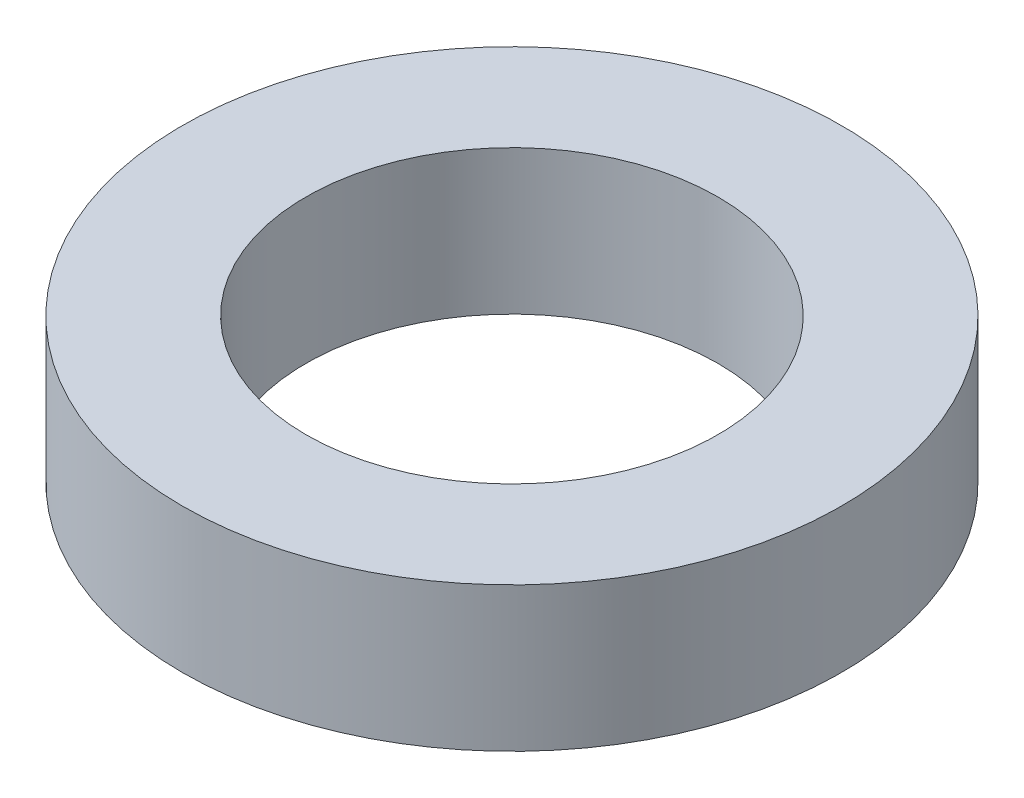
SolidWorks part; units mm, degrees
ref_plane "Front Plane" through (0, 0, 0) normal (0, 0, 1) x (1, 0, 0)
ref_plane "Top Plane" through (0, 0, 0) normal (0, 1, 0) x (1, 0, 0)
ref_plane "Right Plane" through (0, 0, 0) normal (1, 0, 0) x (0, 0, -1)
sketch "Sketch1" plane through (0, 0, 0) normal (0, 1, 0) x (1, 0, 0)
  circle A0 centre (0, 0) radius 16
  circle A1 centre (0, 0) radius 10
  dimension "D1" = 20
  dimension "D2" = 32
extrude "Boss-Extrude1" add sketch "Sketch1" along normal mid plane 7
equation "\"Ns\"= 20"
equation "\"Np_b\"= 26"
equation "\"Np_s\"= 22"
equation "\"Nr_b\"= \"Ns\" + \"Np_b\" * 2"
equation "\"num_planet\"= 4"
equation "\"module\"= 1"
equation "\"fw_p_b\"= 8"
equation "\"fw_r_b\"= \"fw_p_b\"'face width"
equation "\"fw_s_calc\"= 10mm'face width"
equation "\"fw_r_s\"= 8mm'face width"
equation "\"fw_p_s\"= \"fw_r_s\" + \"clearance_planet\""
equation "\"fw_s_used\"= \"fw_p_s\" + \"fw_p_b\" + \"clearance_planet\" + \"sec_carrier_thickness\" + \"standard_clearance_1_5mm\" - \"carrier_small_ring_inner_bearing_flap\" +  \"standard_clearance_1_5mm\" "
equation "\"pressure_angle\"= 20deg"
equation "\"motor_OD\"= 72"
equation "\"motor_height\"= 27"
equation "\"motor_mount_hole_PCD\"= 32"
equation "\"motor_mount_hole_dia\"= 4"
equation "\"motor_mount_hole_num\"= 4"
equation "\"wire_slot_dist_from_center\"= 33"
equation "\"wire_slot_length\"= 10"
equation "\"wire_slot_radius\"= 4"
equation "\"motor_output_hole_PCD\"= 22"
equation "\"motor_output_hole_dia\"= 3"
equation "\"motor_output_hole_num\"= 4"
equation "\"h_a\"= 1 * \"module\"'addendum"
equation "\"h_f\"= 1.25 * \"module\"'dedendum"
equation "\"clr_tip_root\"= \"h_f\" - \"h_a\"'clearance of gear tooth tip and root"
equation "\"dp_r_b\"= \"module\" * \"Nr_b\"'PCD"
equation "\"db_r_b\"= \"dp_r_b\" * cos ( \"pressure_angle\" )'base CD"
equation "\"alpha_r_b\"= sqr ( \"dp_r_b\" ^ 2 - \"db_r_b\" ^ 2 ) / \"db_r_b\" * 180 / pi - \"pressure_angle\""
equation "\"beta_r_b\"= ( 360 / ( 4 * \"Nr_b\" ) + \"alpha_r_b\" ) * 2"
equation "\"bearing_ID\"= \"module\" * ( \"Ns\" + \"Np_b\") + 6"
equation "\"bearing_OD\"= 1.18 * \"bearing_ID\" + 8.57"
equation "\"bearing_height\"= 0.09 * \"bearing_ID\" + 4.62"
equation "\"clearance_planet\"=1.5"
equation "\"case_dist\"= \"sec_carrier_thickness\" + \"clearance_planet\" + \"sun_coupler_hub_thickness\" - \"case_mounting_surface_height\""
equation "\"Motor_case_OD_max\"= \"case_mounting_PCD\" + \"case_mounting_hole_allen_socket_dia\" + \"clearance_case_mount_holes_shell_thickness\" * 2"
equation "\"case_mounting_PCD\"= \"motor_case_OD_base\" + \"case_mounting_hole_shift\" * 2"
equation "\"bearing mount thickness\"= IIF((\"bearing_OD\" + \"output_mounting_hole_dia\" * 4) > (\"Nr_s\" * \"module\" + 2 * \"h_b\"), \"output_mounting_hole_dia\" * 2, ((\"Nr_s\" * \"module\" + 2 * \"h_b\" - (\"bearing_OD\" + \"output_mounting_hole_dia\" * 4)) / 2) + \"output_mounting_hole_dia\" * 2 + \"standard_clearance_1_5mm\")"
equation "\"case_mounting_hole_dia\"=3"
equation "\"output_mounting_PCD\"= \"bearing_OD\" + \"bearing mount thickness\""
equation "\"output_mounting_hole_dia\"= 4"
equation "\"clearance_case_mount_holes_shell_thickness\"= 1"
equation "\"motor_case_OD_base\"= \"motor_OD\" + \"clearance_motor_and_case\" * 2 + \"Motor_case_thickness\" * 2"
equation "\"sec_carrier_thickness\"= 5"
equation "\"sun_coupler_hub_thickness\"= 4"
equation "\"clearance_sun_coupler_sec_carrier\"= 1.5"
equation "\"clearance_motor_and_case\"= IIF( ((\"Ns\" + \"Np_b\" * 2) * \"module\") < \"motor_OD\", 5, (((\"Ns\" + \"Np_b\" * 2) * \"module\" - \"motor_OD\") * 0.5 + 5) )"
equation "\"Motor_case_thickness\"= 2.5"
equation "\"Motor_case_ID\"= \"motor_OD\" + \"clearance_motor_and_case\" * 2"
equation "\"case_mounting_hole_shift\"= \"case_mounting_hole_dia\" / 2 - 0.5"
equation "\"output_mounting_nut_wrench_size\"= 7"
equation "\"output_mounting_nut_thickness\"= 3.2"
equation "\"case_mounting_hole_allen_socket_dia\"= 5.5"
equation "\"output_mounting_nut_depth\"= 3"
equation "\"case_mounting_bolt_depth\"= 4.5"
equation "\"ring_radial_thickness\"= 5"
equation "\"ring_OD_b\"= \"Nr_b\" * \"module\" + \"ring_radial_thickness\" * 2"
equation "\"ring_to_chamfer_clearance\"= \"clearance_planet\""
equation "\"Motor_case_OD_base_to_chamfer\"=5"
equation "\"pattern_offset_from_motor_case_OD_base\"= 3"
equation "\"pattern_bulge_dia\"= 3"
equation "\"pattern_num_bulge\"= 18"
equation "\"pattern_depth\"= 2"
equation "\"case_mounting_wrench_size\"= 5.5"
equation "\"case_mounting_nut_clearance\"= 2"
equation "\"base_plate_thickness\"= 4"
equation "\"case_mounting_nut_thickness\"= 2.4"
equation "\"case_mounting_surface_height\"= 4"
equation "\"central_hole_offset_from_motor_mount_PCD\"= 5"
equation "\"driver_upper_holes_dist_from_center\"= 23"
equation "\"driver_lower_holes_dist_from_center\"= 15"
equation "\"driver_side_holes_dist_from_center\"= 20"
equation "\"driver_mount_holes_dia\"= 2.5"
equation "\"driver_mount_inserts_OD\"= 3.5"
equation "\"driver_mount_thickness\"= 1.5"
equation "\"driver_mount_height\"= 4"
equation "\"air_flow_hole_offset\"= 3"
equation "\"pressure angle\"= 20deg"
equation "\"h_b\"= 1.25 * \"module\"'dedendum"
equation "\"planet_pin_bolt_dia\"= 5"
equation "\"planet_pin_socket_head_dia\"= 8.5"
equation "\"carrier_PCD\"= ( \"Np_b\" + \"Ns\" ) * \"module\""
equation "\"planet_shaft_dia\"= 8"
equation "\"planet_shaft_step_offset\"= 1"
equation "\"carrier_trapezoidal_support_sun_offset\"= 5"
equation "\"carrier_trapezoidal_support_hole_PCD_offset_bearing_ID\"= 4"
equation "\"carrier_trapezoidal_support_hole_dia\"= 3"
equation "\"carrier_trapezoidal_support_hole_socket_head_dia\"= 5.5"
equation "\"carrier_bearing_step_width\"= 1.5"
equation "\"standard_clearance_1_5mm\"=1.5"
equation "\"standard_fillet_1_5mm\"= 1.5"
equation "\"sun_shaft_bearing_ID\"= 8"
equation "\"sun_shaft_bearing_OD\"= 12"
equation "\"sun_shaft_bearing_width\"= 3.5"
equation "\"standard_bearing_insertion_chamfer\"= 0.5"
equation "\"carrier_trapezoidal_support_hole_wrench_size\"= 5.5"
equation "\"planet_pin_bolt_wrench_size\"= 8"
equation "\"planet_bearing_OD\"= 12"
equation "\"planet_bearing_width\"= 3.5"
equation "\"planet_bore\"= 10"
equation "\"dp_s\"= \"module\" * \"Ns\"'PCD"
equation "\"db_s\"= \"dp_s\" * cos ( \"pressure angle\" )'base CD"
equation "\"alpha_s\"= sqr ( \"dp_s\" ^ 2 - \"db_s\" ^ 2 ) / \"db_s\" * 180 / pi - \"pressure angle\""
equation "\"beta_s\"= ( 360 / ( 4 * \"Ns\" ) - \"alpha_s\" ) * 2"
equation "\"dp_p_b\"= \"module\" * \"Np_b\"'PCD"
equation "\"db_p_b\"= \"dp_p_b\" * cos ( \"pressure angle\" )'base CD"
equation "\"alpha_p_b\"= sqr ( \"dp_p_b\" ^ 2 - \"db_p_b\" ^ 2 ) / \"db_p_b\" * 180 / pi - \"pressure angle\""
equation "\"beta_p_b\"= ( 360 / ( 4 * \"Np_b\" ) - \"alpha_p_b\" ) * 2"
equation "\"sun_hub_dia\"= \"motor_output_hole_PCD\" + \"motor_output_hole_dia\" + \"standard_clearance_1_5mm\" * 2"
equation "\"sun_central_bolt_dia\"= 5"
equation "\"sun_central_bolt_socket_head_dia\"= 8.5"
equation "\"motor_output_hole_CSK_OD\"= 9'8.96 is exact value"
equation "\"motor_output_hole_CSK_head_height\"= 2.5"
equation "\"bearing_retainer_thickness\"= 2"
equation "\"dp_p_s\"= \"module\" * \"Np_s\"'PCD"
equation "\"db_p_s\"= \"dp_p_s\" * cos ( \"pressure angle\" )'base CD"
equation "\"alpha_p_s\"= sqr ( \"dp_p_s\" ^ 2 - \"db_p_s\" ^ 2 ) / \"db_p_s\" * 180 / pi - \"pressure angle\""
equation "\"beta_p_s\"= ( 360 / ( 4 * \"Np_s\" ) - \"alpha_p_s\" ) * 2"
equation "\"Nr_s\"= \"Ns\" + \"Np_b\" + \"Np_s\"'num teeth"
equation "\"clr_tip_root_s\"= \"h_f\" - \"h_a\"'clearance of gear tooth tip and root"
equation "\"dp_r_s\"= \"module\" * \"Nr_s\"'PCD"
equation "\"db_r_s\"= \"dp_r_s\" * cos ( \"pressure_angle\" )'base CD"
equation "\"alpha_r_s\"= sqr ( \"dp_r_s\" ^ 2 - \"db_r_s\" ^ 2 ) / \"db_r_s\" * 180 / pi - \"pressure_angle\""
equation "\"beta_r_s\"= ( 360 / ( 4 * \"Nr_s\" ) + \"alpha_r_s\" ) * 2"
equation "\"small_ring_case_thickness\"= 4mm"
equation "\"carrier_thickness\"= 4mm"
equation "\"small_ring_output_wall_thickness\"= 5mm"
equation "\"small_ring_output_wall_to_bearing_shaft_attachement_hole_dia\"= 4mm"
equation "\"small_ring_output_wall_to_bearing_shaft_attachement_hole_depth\"= 6.5mm"
equation "\"small_ring_output_wall_to_bearing_shaft_attachement_nut_wrench\"= 7mm"
equation "\"small_ring_output_wall_to_bearing_shaft_attachement_nut_thickness\"= 3.2mm"
equation "\"small_ring_output_wall_to_bearing_shaft_attachement_hole_pcd\"= 12mm"
equation "\"small_ring_output_wall_to_bearing_shaft_attachement_hole_num\"= 3"
equation "\"small_ring_output_wall_to_bearing_shaft_attachement_hole_CSK_OD\"= 9mm"
equation "\"small_ring_output_wall_to_bearing_shaft_attachement_hole_CSK_head_height\"= 2.5mm"
equation "\"carrier_small_ring_inner_bearing_ID\"= 20mm"
equation "\"carrier_small_ring_inner_bearing_OD\"= 32mm"
equation "\"carrier_small_ring_inner_bearing_height\"= 7mm"
equation "\"carrier_small_ring_inner_bearing_flap\"= 2mm"
equation "\"D1@Boss-Extrude1\"=\"carrier_small_ring_inner_bearing_height\""
equation "\"D1@Sketch1\"=\"carrier_small_ring_inner_bearing_ID\""
equation "\"D2@Sketch1\"=\"carrier_small_ring_inner_bearing_OD\""
